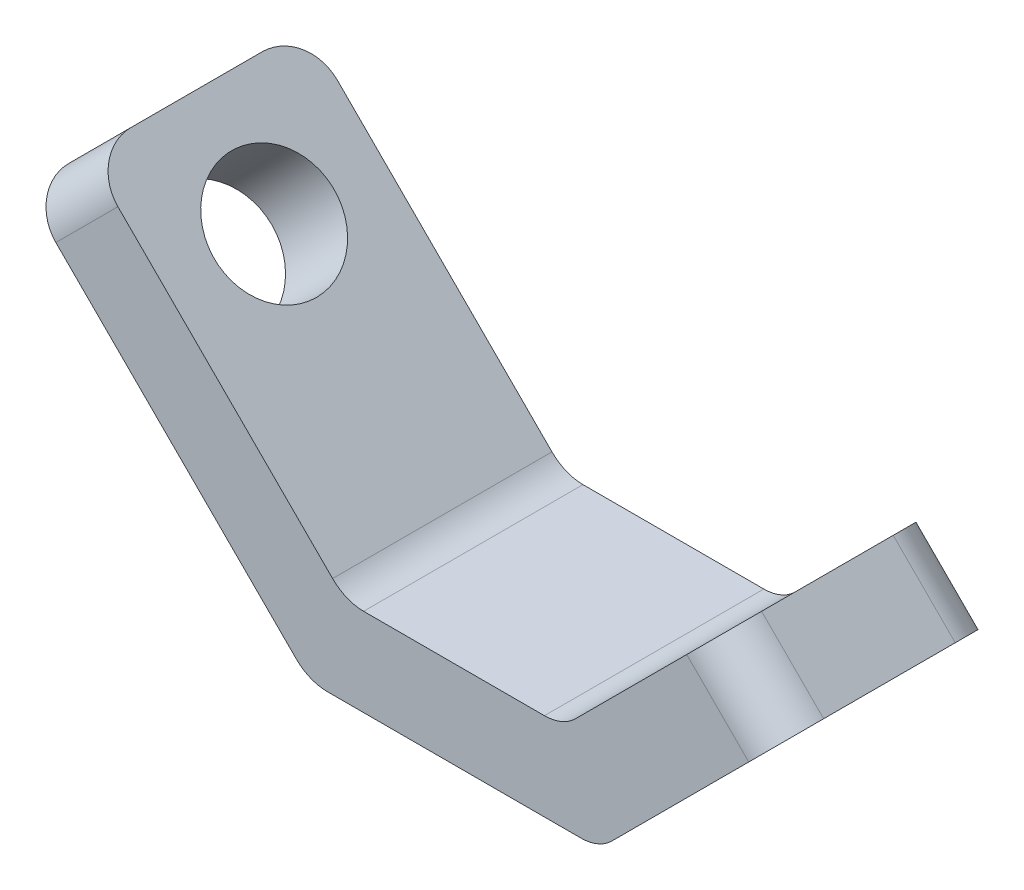
SolidWorks part; units mm, degrees
ref_plane "正面" through (0, 0, 0) normal (0, 0, 1) x (1, 0, 0)
ref_plane "平面" through (0, 0, 0) normal (0, 1, 0) x (1, 0, 0)
ref_plane "右側面" through (0, 0, 0) normal (1, 0, 0) x (0, 0, -1)
sketch "ｽｹｯﾁ1" plane through (0, 0, 0) normal (0, 0, 1) x (1, 0, 0)
  line L0 (0, 0) -> (-19.435, 19.435)
  line L1 (-19.435, 19.435) -> (-15.1924, 23.6777)
  line L2 (-15.1924, 23.6777) -> (2.4853, 6)
  line L3 (2.4853, 6) -> (17.3345, 6)
  line L4 (17.3345, 6) -> (27.9411, 16.6066)
  line L5 (27.9411, 16.6066) -> (32.1838, 12.364)
  line L6 (32.1838, 12.364) -> (19.8198, 0)
  line L7 (19.8198, 0) -> (0, 0)
  point P6 (22.6378, 11.3033)
  dimension "D1" = 135
  dimension "D2" = 135
  dimension "D3" = 6
  dimension "D4" = 6
  dimension "D5" = 6
  dimension "D6" = 25
  dimension "D7" = 15
  dimension "D8" = 18
extrude "ﾎﾞｽ - 押し出し1" add sketch "ｽｹｯﾁ1" along normal mid plane 15
sketch "ｽｹｯﾁ2" plane through (0, 0, 0) normal (-0.7071, -0.7071, 0) x (0, 0, 1)
  line L1 (7.5, 27.4853) -> (-7.5, 27.4853) construction
  circle A0 centre (0, 19.9853) radius 4.1
  point P2 (0, 0)
  dimension "D1" = 8.2
  dimension "D2" = 7.5
extrude "ｶｯﾄ - 押し出し1" cut sketch "ｽｹｯﾁ2" against normal through all both and the other way through all
sketch "ｽｹｯﾁ3" plane through (9.9099, -9.9099, 0) normal (0.7071, -0.7071, 0) x (0, 0, -1)
  line L0 (-7.5, 31.5) -> (-7.5, 16.5) construction
  line L1 (-7.5, 31.5) -> (7.5, 31.5) construction
  circle A0 centre (0, 24) radius 4.1
  point P4 (-7.5, 24)
  point P7 (0, 31.5)
  dimension "D1" = 8.2
extrude "ｶｯﾄ - 押し出し2" cut sketch "ｽｹｯﾁ3" against normal through all both and the other way through all
fillet "ﾌｨﾚｯﾄ1" radius 3 8 edges at (30.0624, 14.4853, -7.5) (30.0624, 14.4853, 7.5) (-17.3137, 21.5563, -7.5) (-17.3137, 21.5563, 7.5) (19.8198, 0, 0) (0, 0, 0) (17.3345, 6, 0) (2.4853, 6, 0)
equation "\"D4@ｽｹｯﾁ1\"=\"D3@ｽｹｯﾁ1\""
equation "\"D5@ｽｹｯﾁ1\"=\"D3@ｽｹｯﾁ1\""
